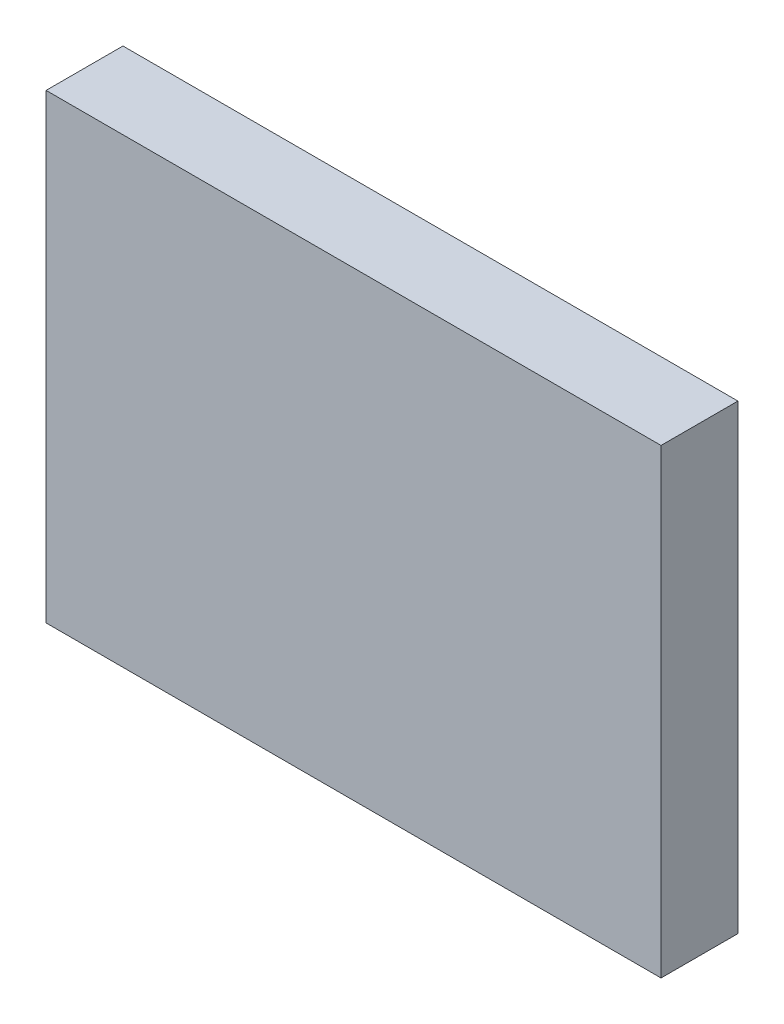
SolidWorks part; units mm, degrees
ref_plane "Front Plane" through (0, 0, 0) normal (0, 0, 1) x (1, 0, 0)
ref_plane "Top Plane" through (0, 0, 0) normal (0, 1, 0) x (1, 0, 0)
ref_plane "Right Plane" through (0, 0, 0) normal (1, 0, 0) x (0, 0, -1)
sketch "Sketch1" plane through (0, 0, 0) normal (0, 0, 1) x (1, 0, 0)
  line L1 (0, 0) -> (101.6, 0)
  line L2 (0, 0) -> (0, 76.2)
  line L3 (0, 76.2) -> (101.6, 76.2)
  line L4 (101.6, 0) -> (101.6, 76.2)
extrude "Boss-Extrude1" add sketch "Sketch1" along normal blind 12.7
